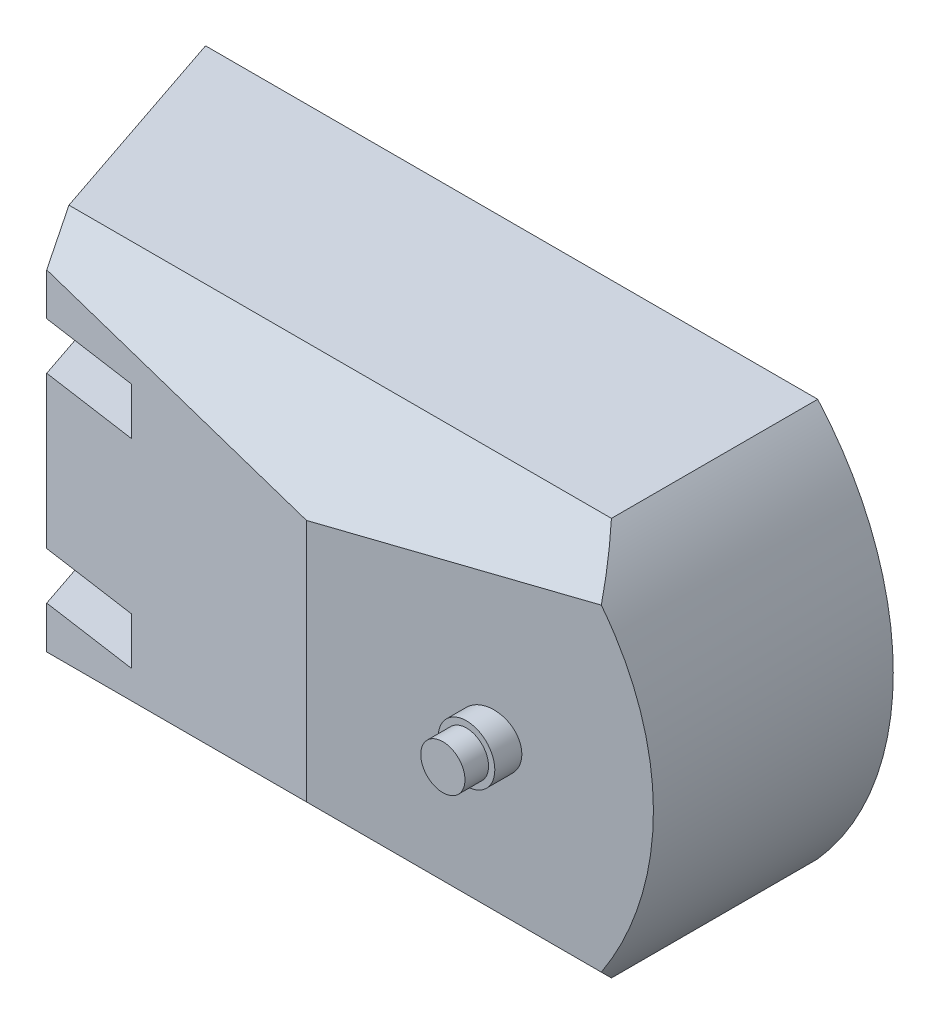
SolidWorks part; units mm, degrees
material "Alloy Steel"
ref_plane "Front Plane" through (0, 0, 0) normal (0, 0, 1) x (1, 0, 0)
ref_plane "Top Plane" through (0, 0, 0) normal (0, 1, 0) x (1, 0, 0)
ref_plane "Right Plane" through (0, 0, 0) normal (1, 0, 0) x (0, 0, -1)
sketch "Sketch1" plane through (0, 0, 0) normal (0, 0, 1) x (1, 0, 0)
  line L1 (-18658.5503, 10876.7229) -> (-25135.3672, 10876.7229)
  line L2 (-25135.3672, 10876.7229) -> (-25135.3672, 15090.402)
  line L3 (-25135.3672, 15090.402) -> (-18658.5503, 15090.402)
  arc A1 (-18658.5503, 10876.7229) -> (-18658.5503, 15090.402) centre (-21033.8086, 12983.5624) ccw
  dimension "D1" = 3175
extrude "Boss-Extrude1" add sketch "Sketch1" along normal blind 3000
ref_plane "Plane1" through (0, 12983.5624, 0) normal (0, 1, 0) x (1, 0, 0)
sketch "Sketch2" plane through (0, 12983.5624, 0) normal (0, 1, 0) x (1, 0, 0)
  line L0 (-25139.2062, 0) -> (-24281.0358, -2538.9764)
  line L1 (-18658.5503, 0) -> (-25135.3672, 0) construction
  line L2 (-24281.0358, -2538.9764) -> (-21069.9222, -3000)
  line L3 (-18658.5503, -3000) -> (-25135.3672, -3000) construction
  line L4 (-21069.9222, -3000) -> (-17858.8086, -2538.9764)
  line L5 (-17858.8086, -3000) -> (-17858.8086, 0) construction
  line L6 (-17858.8086, -2538.9764) -> (-17858.8086, -3000)
  line L7 (-18658.5503, -3000) -> (-17858.8086, -3000) construction
  line L8 (-17858.8086, -3000) -> (-25135.3672, -3000)
  line L9 (-25135.3672, -3000) -> (-25139.2062, 0)
  dimension "D1" = 3211.1136
  dimension "D2" = 858.1704
  dimension "D3" = 461.0236
extrude "Cut-Extrude1" cut sketch "Sketch2" against normal through all both and the other way through all contours L8 L6 L4 | L9 L8 L2 L0
ref_plane "Plane2" through (-21069.9222, 0, 0) normal (1, 0, 0) x (0, 0, -1)
sketch "Sketch3" plane through (-21069.9222, 0, 0) normal (1, 0, 0) x (0, 0, -1)
  line L0 (-2183.7339, 15090.402) -> (-3000, 14274.1359)
  line L1 (-11.358, 15090.402) -> (-2538.9764, 15090.402) construction
  line L2 (-3000, 10876.7229) -> (-3000, 15090.402) construction
  line L3 (-3000, 14274.1359) -> (-3000, 15090.402)
  line L4 (-2538.9764, 15090.402) -> (-3000, 15090.402) construction
  line L5 (-3000, 15090.402) -> (-2183.7339, 15090.402)
  line L6 (-11.358, 12983.5624) -> (-3000, 12983.5624) construction
  line L7 (-11.358, 15090.402) -> (-11.358, 10876.7229) construction
  line L8 (-3000, 11692.989) -> (-3000, 10876.7229)
  line L9 (-2183.7339, 10876.7229) -> (-3000, 11692.989)
  line L10 (-3000, 10876.7229) -> (-2183.7339, 10876.7229)
  dimension "D1" = 45
extrude "Cut-Extrude2" cut sketch "Sketch3" against normal through all both and the other way through all
sketch "Sketch4" plane through (0, 0, 0) normal (0, 0, 1) x (1, 0, 0)
  line L0 (-25135.3672, 15090.402) -> (-25135.3672, 10876.7229) construction
  line L1 (-25135.3672, 14286.9822) -> (-23230.3672, 14286.9822)
  line L2 (-25135.3672, 14286.9822) -> (-25135.3672, 13786.9822)
  line L3 (-25135.3672, 13786.9822) -> (-23230.3672, 13786.9822)
  line L4 (-23230.3672, 14286.9822) -> (-23230.3672, 13786.9822)
  line L5 (-25135.3672, 12983.5624) -> (-17858.8086, 12983.5624) construction
  line L6 (-25135.3672, 10876.7229) -> (-25135.3672, 15090.402) construction
  line L7 (-23230.3672, 15090.402) -> (-23230.3672, 12983.5624) construction
  line L9 (-24401.1073, 15090.402) -> (-18658.5503, 15090.402) construction
  line L10 (-25135.3672, 12180.1427) -> (-23230.3672, 12180.1427)
  line L11 (-23230.3672, 11680.1427) -> (-23230.3672, 12180.1427)
  line L12 (-25135.3672, 11680.1427) -> (-23230.3672, 11680.1427)
  line L13 (-25135.3672, 11680.1427) -> (-25135.3672, 12180.1427)
  arc A0 (-18341.1629, 11301.2176) -> (-18341.1629, 14665.9073) centre (-21033.8086, 12983.5624) ccw construction
  point P11 (-23230.3672, 14036.9822)
  point P14 (-25135.3672, 12983.5624)
  point P19 (-23230.3672, 14036.9822)
  dimension "D1" = 500
  dimension "D2" = 1905
extrude "Cut-Extrude3" cut sketch "Sketch4" against normal blind 1500 from offset 3000
sketch "Sketch5" plane through (0, 0, 0) normal (0, 0, 1) x (1, 0, 0)
  line L0 (-17858.8086, 12983.5624) -> (-25135.3672, 12983.5624) construction
  line L1 (-25135.3672, 15090.402) -> (-25135.3672, 10876.7229) construction
  line L2 (-19376.7582, 15090.402) -> (-19376.7582, 10876.7229) construction
  line L3 (-24401.1073, 15090.402) -> (-18658.5503, 15090.402) construction
  line L4 (-24401.1073, 10876.7229) -> (-18658.5503, 10876.7229) construction
  line L5 (-21069.9222, 11692.989) -> (-21069.9222, 14274.1359) construction
  arc A0 (-18341.1629, 11301.2176) -> (-18341.1629, 14665.9073) centre (-21033.8086, 12983.5624) ccw construction
  circle A1 centre (-19376.7582, 12983.5624) radius 300
  dimension "D1" = 1693.164
extrude "Boss-Extrude2" add sketch "Sketch5" along normal blind 3000
sketch "Sketch6" plane through (0, 0, 3000) normal (0, 0, 1) x (1, 0, 0)
  circle A2 centre (-19376.7582, 12983.5624) radius 234
  circle A3 centre (-19376.7582, 12983.5624) radius 234
  dimension "D1" = 66
extrude "Boss-Extrude3" add sketch "Sketch6" along normal blind 250
extrude "Cut-Extrude4" cut sketch "Sketch7" against normal mid plane 3500
sketch "Sketch7" plane through (0, 12983.5624, 0) normal (0, -1, 0) x (-1, 0, 0)
  circle A0 centre (23612.1268, -2183.7339) radius 63.5
sketch "Sketch8" plane through (0, 0, 0) normal (0, 0, -1) x (-1, 0, 0)
  line L0 (25135.3672, 12983.5624) -> (17858.8086, 12983.5624) construction
  line L1 (25135.3672, 15090.402) -> (25135.3672, 10876.7229) construction
  circle A0 centre (20757.1879, 12983.5624) radius 950
  arc A1 (18658.5503, 15090.402) -> (18658.5503, 10876.7229) centre (21033.8086, 12983.5624) ccw construction
  dimension "D1" = 1900
extrude "Boss-Extrude4" add sketch "Sketch8" along normal blind 500
